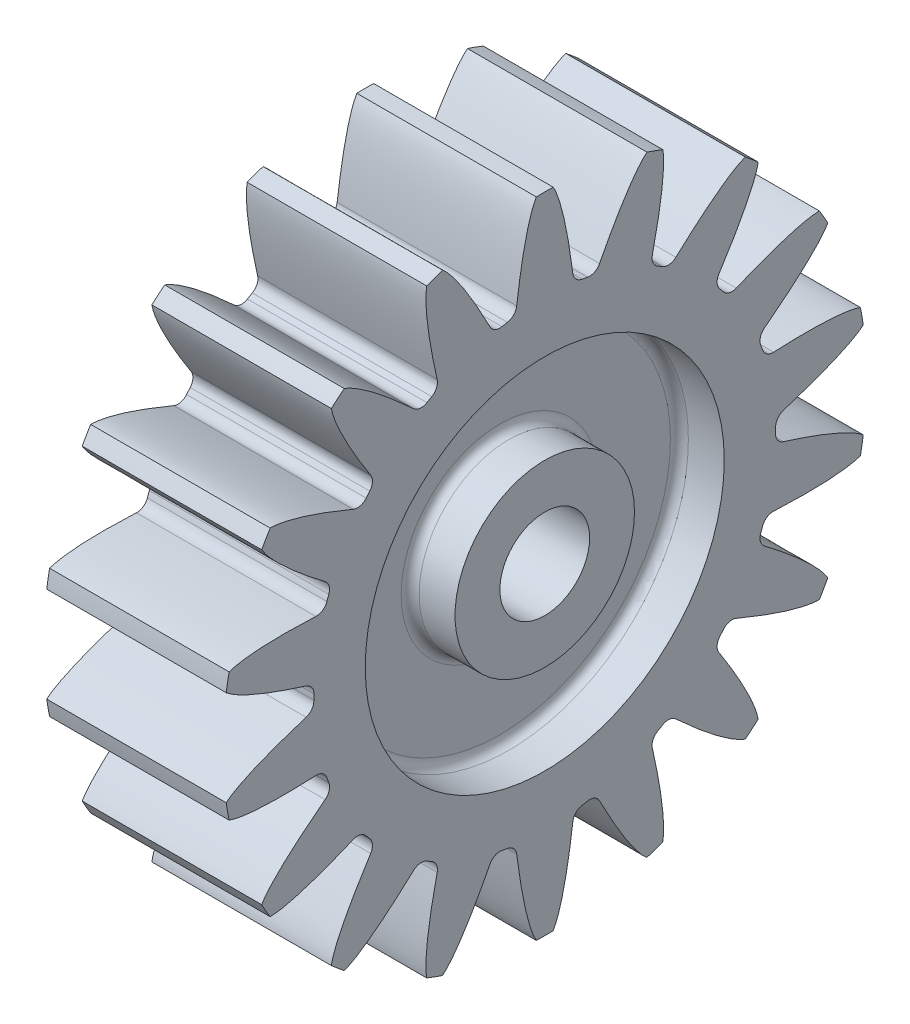
SolidWorks part; units mm, degrees
ref_plane "Front Plane" through (0, 0, 0) normal (0, 0, 1) x (1, 0, 0)
ref_plane "Top Plane" through (0, 0, 0) normal (0, 1, 0) x (1, 0, 0)
ref_plane "Right Plane" through (0, 0, 0) normal (1, 0, 0) x (0, 0, -1)
sketch "Sketch2" plane through (0, 0, 0) normal (1, 0, 0) x (0, 0, -1)
  line L0 (0, 59.4812) -> (0, -59.4812) construction
  line L1 (-82.8846, 0) -> (82.8846, 0) construction
  line L2 (-1.1938, 45.5577) -> (1.1938, 45.5577) construction
  line L3 (-3.3249, 37.9546) -> (3.3249, 37.9546) construction
  line L4 (0, 0) -> (5.736, 0) construction
  line L5 (0, 0) -> (5.3901, -1.9618) construction
  line L6 (9.8569, 36.8029) -> (16.1056, 34.5285) construction
  line L7 (21.8498, 31.2121) -> (26.9438, 26.9378) construction
  line L8 (31.2073, 21.8567) -> (34.5321, 16.0979) construction
  line L9 (36.8007, 9.8651) -> (37.9554, 3.3164) construction
  line L10 (37.9554, -3.3164) -> (36.8007, -9.8651) construction
  line L11 (34.5321, -16.0979) -> (31.2073, -21.8567) construction
  line L12 (26.9438, -26.9378) -> (21.8498, -31.2121) construction
  line L13 (16.1056, -34.5285) -> (9.8569, -36.8029) construction
  line L14 (3.3249, -37.9546) -> (-3.3249, -37.9546) construction
  line L15 (-9.8569, -36.8029) -> (-16.1056, -34.5285) construction
  line L16 (-21.8498, -31.2121) -> (-26.9438, -26.9378) construction
  line L17 (-31.2073, -21.8567) -> (-34.5321, -16.0979) construction
  line L18 (-36.8007, -9.8651) -> (-37.9554, -3.3164) construction
  line L19 (-37.9554, 3.3164) -> (-36.8007, 9.8651) construction
  line L20 (-34.5321, 16.0979) -> (-31.2073, 21.8567) construction
  line L21 (-26.9438, 26.9378) -> (-21.8498, 31.2121) construction
  line L22 (-16.1056, 34.5285) -> (-9.8569, 36.8029) construction
  line L23 (0, 0) -> (3.3249, 37.9546) construction
  line L24 (0, 0) -> (16.1056, 34.5285) construction
  circle A0 centre (0, 0) radius 38.1 construction
  arc A1 (-5.2813, 32.2346) -> (-6.0621, 32.097) centre (0, 0) ccw
  arc A3 (1.1938, 45.5577) -> (-1.1938, 45.5577) centre (0, 0) ccw
  arc A4 (-5.2813, 32.2346) -> (-3.9739, 33.5885) centre (-5.5359, 33.7887) ccw
  arc A5 (5.2813, 32.2346) -> (3.9739, 33.5885) centre (5.5359, 33.7887) cw
  arc A6 (16.7035, 42.402) -> (14.4599, 43.2186) centre (0, 0) ccw
  arc A7 (15.9877, 28.4843) -> (15.2222, 30.2037) centre (16.7585, 29.8576) cw
  arc A8 (6.0621, 32.097) -> (7.7537, 32.922) centre (6.3543, 33.6444) ccw
  arc A9 (30.1984, 34.1319) -> (28.3694, 35.6666) centre (0, 0) ccw
  arc A10 (24.7657, 21.2984) -> (24.6345, 23.1759) centre (25.9597, 22.3252) cw
  arc A11 (16.6743, 28.0879) -> (18.5461, 28.2846) centre (17.4782, 29.4421) ccw
  arc A12 (40.051, 21.745) -> (38.8572, 23.8127) centre (0, 0) ccw
  arc A13 (30.5567, 11.5436) -> (31.0754, 13.3527) centre (32.0298, 12.1001) cw
  arc A14 (25.2753, 20.6911) -> (27.1015, 20.2358) centre (26.4939, 21.6886) ccw
  arc A15 (45.0729, 6.7354) -> (44.6583, 9.0867) centre (0, 0) ccw
  arc A16 (32.662, 0.3964) -> (33.7683, 1.919) centre (34.2367, 0.4155) cw
  arc A17 (30.8278, 10.7986) -> (32.3881, 9.7461) centre (32.3141, 11.3192) ccw
  arc A18 (44.6583, -9.0867) -> (45.0729, -6.7354) centre (0, 0) ccw
  arc A19 (30.8278, -10.7986) -> (32.3881, -9.7461) centre (32.3141, -11.3192) cw
  arc A20 (32.662, -0.3964) -> (33.7683, -1.919) centre (34.2367, -0.4155) ccw
  arc A21 (38.8572, -23.8127) -> (40.051, -21.745) centre (0, 0) ccw
  arc A22 (25.2753, -20.6911) -> (27.1015, -20.2358) centre (26.4939, -21.6886) cw
  arc A23 (30.5567, -11.5436) -> (31.0754, -13.3527) centre (32.0298, -12.1001) ccw
  arc A24 (28.3694, -35.6666) -> (30.1984, -34.1319) centre (0, 0) ccw
  arc A25 (16.6743, -28.0879) -> (18.5461, -28.2846) centre (17.4782, -29.4421) cw
  arc A26 (24.7657, -21.2984) -> (24.6345, -23.1759) centre (25.9597, -22.3252) ccw
  arc A27 (14.4599, -43.2186) -> (16.7035, -42.402) centre (0, 0) ccw
  arc A28 (6.0621, -32.097) -> (7.7537, -32.922) centre (6.3543, -33.6444) cw
  arc A29 (15.9877, -28.4843) -> (15.2222, -30.2037) centre (16.7585, -29.8576) ccw
  arc A30 (-1.1938, -45.5577) -> (1.1938, -45.5577) centre (0, 0) ccw
  arc A31 (-5.2813, -32.2346) -> (-3.9739, -33.5885) centre (-5.5359, -33.7887) cw
  arc A32 (5.2813, -32.2346) -> (3.9739, -33.5885) centre (5.5359, -33.7887) ccw
  arc A33 (-16.7035, -42.402) -> (-14.4599, -43.2186) centre (0, 0) ccw
  arc A34 (-15.9877, -28.4843) -> (-15.2222, -30.2037) centre (-16.7585, -29.8576) cw
  arc A35 (-6.0621, -32.097) -> (-7.7537, -32.922) centre (-6.3543, -33.6444) ccw
  arc A36 (-30.1984, -34.1319) -> (-28.3694, -35.6666) centre (0, 0) ccw
  arc A37 (-24.7657, -21.2984) -> (-24.6345, -23.1759) centre (-25.9597, -22.3252) cw
  arc A38 (-16.6743, -28.0879) -> (-18.5461, -28.2846) centre (-17.4782, -29.4421) ccw
  arc A39 (-40.051, -21.745) -> (-38.8572, -23.8127) centre (0, 0) ccw
  arc A40 (-30.5567, -11.5436) -> (-31.0754, -13.3527) centre (-32.0298, -12.1001) cw
  arc A41 (-25.2753, -20.6911) -> (-27.1015, -20.2358) centre (-26.4939, -21.6886) ccw
  arc A42 (-45.0729, -6.7354) -> (-44.6583, -9.0867) centre (0, 0) ccw
  arc A43 (-32.662, -0.3964) -> (-33.7683, -1.919) centre (-34.2367, -0.4155) cw
  arc A44 (-30.8278, -10.7986) -> (-32.3881, -9.7461) centre (-32.3141, -11.3192) ccw
  arc A45 (-44.6583, 9.0867) -> (-45.0729, 6.7354) centre (0, 0) ccw
  arc A46 (-30.8278, 10.7986) -> (-32.3881, 9.7461) centre (-32.3141, 11.3192) cw
  arc A47 (-32.662, 0.3964) -> (-33.7683, 1.919) centre (-34.2367, 0.4155) ccw
  arc A48 (-38.8572, 23.8127) -> (-40.051, 21.745) centre (0, 0) ccw
  arc A49 (-25.2753, 20.6911) -> (-27.1015, 20.2358) centre (-26.4939, 21.6886) cw
  arc A50 (-30.5567, 11.5436) -> (-31.0754, 13.3527) centre (-32.0298, 12.1001) ccw
  arc A51 (-28.3694, 35.6666) -> (-30.1984, 34.1319) centre (0, 0) ccw
  arc A52 (-16.6743, 28.0879) -> (-18.5461, 28.2846) centre (-17.4782, 29.4421) cw
  arc A53 (-24.7657, 21.2984) -> (-24.6345, 23.1759) centre (-25.9597, 22.3252) ccw
  arc A54 (-14.4599, 43.2186) -> (-16.7035, 42.402) centre (0, 0) ccw
  arc A55 (-6.0621, 32.097) -> (-7.7537, 32.922) centre (-6.3543, 33.6444) cw
  arc A56 (-15.9877, 28.4843) -> (-15.2222, 30.2037) centre (-16.7585, 29.8576) ccw
  arc A57 (-15.9877, 28.4843) -> (-16.6743, 28.0879) centre (0, 0) ccw
  arc A58 (-24.7657, 21.2984) -> (-25.2753, 20.6911) centre (0, 0) ccw
  arc A59 (6.0621, 32.097) -> (5.2813, 32.2346) centre (0, 0) ccw
  arc A60 (16.6743, 28.0879) -> (15.9877, 28.4843) centre (0, 0) ccw
  arc A61 (25.2753, 20.6911) -> (24.7657, 21.2984) centre (0, 0) ccw
  arc A62 (30.8278, 10.7986) -> (30.5567, 11.5436) centre (0, 0) ccw
  arc A63 (32.662, -0.3964) -> (32.662, 0.3964) centre (0, 0) ccw
  arc A64 (30.5567, -11.5436) -> (30.8278, -10.7986) centre (0, 0) ccw
  arc A65 (24.7657, -21.2984) -> (25.2753, -20.6911) centre (0, 0) ccw
  arc A66 (15.9877, -28.4843) -> (16.6743, -28.0879) centre (0, 0) ccw
  arc A67 (5.2813, -32.2346) -> (6.0621, -32.097) centre (0, 0) ccw
  arc A68 (-6.0621, -32.097) -> (-5.2813, -32.2346) centre (0, 0) ccw
  arc A69 (-16.6743, -28.0879) -> (-15.9877, -28.4843) centre (0, 0) ccw
  arc A70 (-25.2753, -20.6911) -> (-24.7657, -21.2984) centre (0, 0) ccw
  arc A71 (-30.8278, -10.7986) -> (-30.5567, -11.5436) centre (0, 0) ccw
  arc A72 (-32.662, 0.3964) -> (-32.662, -0.3964) centre (0, 0) ccw
  arc A73 (-30.5567, 11.5436) -> (-30.8278, 10.7986) centre (0, 0) ccw
  circle A74 centre (0, 0) radius 25.4
  circle A75 centre (0, 0) radius 12.7
  circle A76 centre (0, 0) radius 6.35
  ellipse E0 centre (0, 0) end of major axis (0, -46.5777) minor radius 5.736 (-1.1938, 45.5577) -> (-3.9739, 33.5885) ccw
  ellipse E1 centre (0, 0) end of major axis (0, -46.5777) minor radius 5.736 (3.9739, 33.5885) -> (1.1938, 45.5577) ccw
  ellipse E2 centre (0, 0) end of major axis (-15.9305, -43.7687) minor radius 5.736 (14.4599, 43.2186) -> (7.7537, 32.922) ccw
  ellipse E3 centre (0, 0) end of major axis (-15.9305, -43.7687) minor radius 5.736 (15.2222, 30.2037) -> (16.7035, 42.402) ccw
  ellipse E4 centre (0, 0) end of major axis (-29.9395, -35.6806) minor radius 5.736 (28.3694, 35.6666) -> (18.5461, 28.2846) ccw
  ellipse E5 centre (0, 0) end of major axis (-29.9395, -35.6806) minor radius 5.736 (24.6345, 23.1759) -> (30.1984, 34.1319) ccw
  ellipse E6 centre (0, 0) end of major axis (-40.3374, -23.2888) minor radius 5.736 (38.8572, 23.8127) -> (27.1015, 20.2358) ccw
  ellipse E7 centre (0, 0) end of major axis (-40.3374, -23.2888) minor radius 5.736 (31.0754, 13.3527) -> (40.051, 21.745) ccw
  ellipse E8 centre (0, 0) end of major axis (-45.87, -8.0881) minor radius 5.736 (44.6583, 9.0867) -> (32.3881, 9.7461) ccw
  ellipse E9 centre (0, 0) end of major axis (-45.87, -8.0881) minor radius 5.736 (33.7683, 1.919) -> (45.0729, 6.7354) ccw
  ellipse E10 centre (0, 0) end of major axis (-45.87, 8.0881) minor radius 5.736 (45.0729, -6.7354) -> (33.7683, -1.919) ccw
  ellipse E11 centre (0, 0) end of major axis (-45.87, 8.0881) minor radius 5.736 (32.3881, -9.7461) -> (44.6583, -9.0867) ccw
  ellipse E12 centre (0, 0) end of major axis (-40.3374, 23.2888) minor radius 5.736 (40.051, -21.745) -> (31.0754, -13.3527) ccw
  ellipse E13 centre (0, 0) end of major axis (-40.3374, 23.2888) minor radius 5.736 (27.1015, -20.2358) -> (38.8572, -23.8127) ccw
  ellipse E14 centre (0, 0) end of major axis (-29.9395, 35.6806) minor radius 5.736 (30.1984, -34.1319) -> (24.6345, -23.1759) ccw
  ellipse E15 centre (0, 0) end of major axis (-29.9395, 35.6806) minor radius 5.736 (18.5461, -28.2846) -> (28.3694, -35.6666) ccw
  ellipse E16 centre (0, 0) end of major axis (-15.9305, 43.7687) minor radius 5.736 (16.7035, -42.402) -> (15.2222, -30.2037) ccw
  ellipse E17 centre (0, 0) end of major axis (-15.9305, 43.7687) minor radius 5.736 (7.7537, -32.922) -> (14.4599, -43.2186) ccw
  ellipse E18 centre (0, 0) end of major axis (0, 46.5777) minor radius 5.736 (1.1938, -45.5577) -> (3.9739, -33.5885) ccw
  ellipse E19 centre (0, 0) end of major axis (0, 46.5777) minor radius 5.736 (-3.9739, -33.5885) -> (-1.1938, -45.5577) ccw
  ellipse E20 centre (0, 0) end of major axis (15.9305, 43.7687) minor radius 5.736 (-14.4599, -43.2186) -> (-7.7537, -32.922) ccw
  ellipse E21 centre (0, 0) end of major axis (15.9305, 43.7687) minor radius 5.736 (-15.2222, -30.2037) -> (-16.7035, -42.402) ccw
  ellipse E22 centre (0, 0) end of major axis (29.9395, 35.6806) minor radius 5.736 (-28.3694, -35.6666) -> (-18.5461, -28.2846) ccw
  ellipse E23 centre (0, 0) end of major axis (29.9395, 35.6806) minor radius 5.736 (-24.6345, -23.1759) -> (-30.1984, -34.1319) ccw
  ellipse E24 centre (0, 0) end of major axis (40.3374, 23.2888) minor radius 5.736 (-38.8572, -23.8127) -> (-27.1015, -20.2358) ccw
  ellipse E25 centre (0, 0) end of major axis (40.3374, 23.2888) minor radius 5.736 (-31.0754, -13.3527) -> (-40.051, -21.745) ccw
  ellipse E26 centre (0, 0) end of major axis (45.87, 8.0881) minor radius 5.736 (-44.6583, -9.0867) -> (-32.3881, -9.7461) ccw
  ellipse E27 centre (0, 0) end of major axis (45.87, 8.0881) minor radius 5.736 (-33.7683, -1.919) -> (-45.0729, -6.7354) ccw
  ellipse E28 centre (0, 0) end of major axis (45.87, -8.0881) minor radius 5.736 (-45.0729, 6.7354) -> (-33.7683, 1.919) ccw
  ellipse E29 centre (0, 0) end of major axis (45.87, -8.0881) minor radius 5.736 (-32.3881, 9.7461) -> (-44.6583, 9.0867) ccw
  ellipse E30 centre (0, 0) end of major axis (40.3374, -23.2888) minor radius 5.736 (-40.051, 21.745) -> (-31.0754, 13.3527) ccw
  ellipse E31 centre (0, 0) end of major axis (40.3374, -23.2888) minor radius 5.736 (-27.1015, 20.2358) -> (-38.8572, 23.8127) ccw
  ellipse E32 centre (0, 0) end of major axis (29.9395, -35.6806) minor radius 5.736 (-30.1984, 34.1319) -> (-24.6345, 23.1759) ccw
  ellipse E33 centre (0, 0) end of major axis (29.9395, -35.6806) minor radius 5.736 (-18.5461, 28.2846) -> (-28.3694, 35.6666) ccw
  ellipse E34 centre (0, 0) end of major axis (15.9305, -43.7687) minor radius 5.736 (-16.7035, 42.402) -> (-15.2222, 30.2037) ccw
  ellipse E35 centre (0, 0) end of major axis (15.9305, -43.7687) minor radius 5.736 (-7.7537, 32.922) -> (-14.4599, 43.2186) ccw
  dimension "D1" = 76.2
  dimension "D2" = 65.3288
  dimension "D3" = 1.5748
  dimension "D6" = 1.5748
  dimension "D11" = 3.8381
  dimension "D16" = 50.8
  dimension "D17" = 25.4
  dimension "D18" = 12.7
  dimension "D4" = 2.3876
  dimension "D5" = 6.6497
  dimension "D7" = 7.9478
  dimension "D9" = 20
  dimension "D10" = 5.736
  dimension "D12" = 18
  dimension "D13" = 20
  dimension "D14" = 38.1
  dimension "D15" = 6.6328
  dimension "D8" = 18
extrude "Boss-Extrude5" add sketch "Sketch2" along normal mid plane 25.4 contours A55 E35 A54 E34 A56 A57 A52 E33 A51 E32 A53 A58 A49 E31 A48 E30 A50 A73 A46 E29 A45 E28 A47 A72 A43 E27 A42 E26 A44 A71 A40 E25 A39 E24 A41 A70 A37 E23 A36 E22 A38 A69 A34 E21 A33 E20 A35 A68 A31 E19 A30 | A74 A75 | A75 A76
sketch "Sketch4" plane through (12.7, 0, 0) normal (1, 0, 0) x (0, 0, -1)
  circle A0 centre (0, 0) radius 25.4
  circle A1 centre (0, 0) radius 12.7
extrude "Cut-Extrude2" cut sketch "Sketch4" against normal blind 6.35
mirror "Mirror2" about plane through (0, 0, 0) normal (1, 0, 0) of "Cut-Extrude2"
fillet "Fillet1" radius 1.27 2 edges at (6.35, 0, -25.4) (-6.35, 0, -25.4)
fillet "Fillet2" radius 1.27 2 edges at (6.35, 0, -12.7) (-6.35, 0, -12.7)
